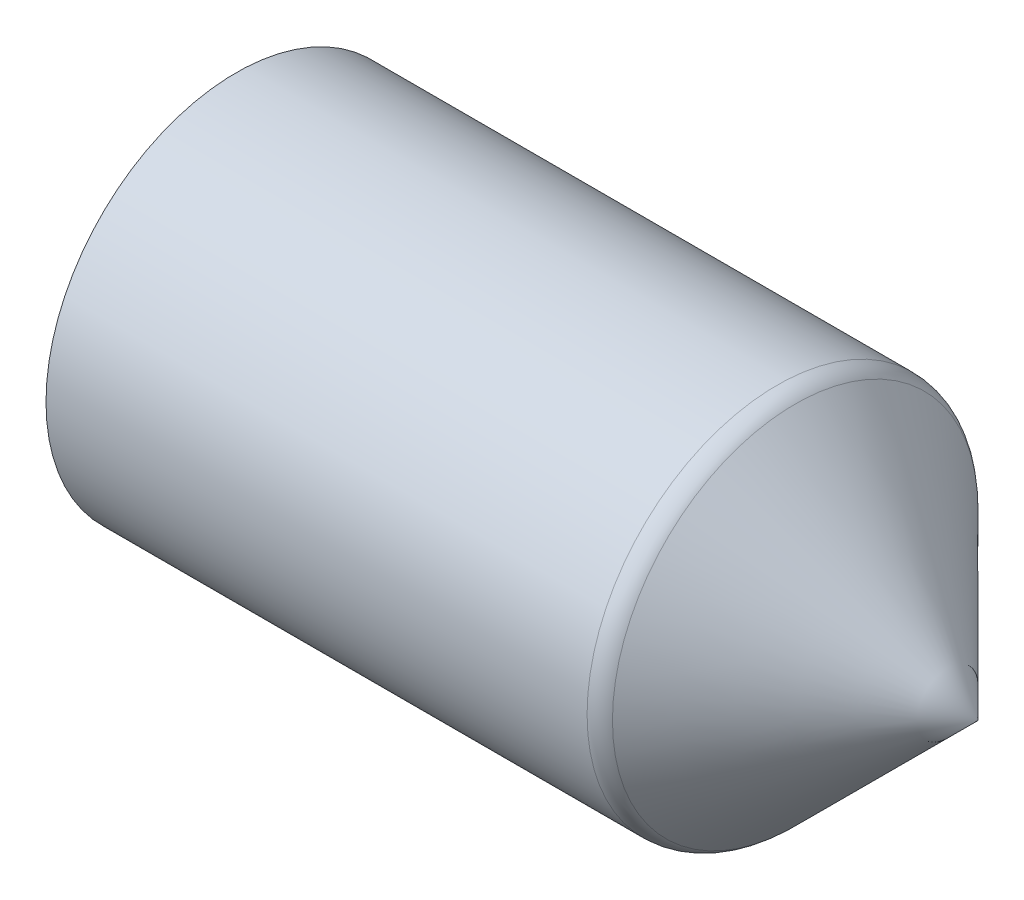
SolidWorks part; units mm, degrees
ref_plane "Front Plane" through (0, 0, 0) normal (0, 0, 1) x (1, 0, 0)
ref_plane "Top Plane" through (0, 0, 0) normal (0, 1, 0) x (1, 0, 0)
ref_plane "Right Plane" through (0, 0, 0) normal (1, 0, 0) x (0, 0, -1)
sketch "Sketch1" plane through (0, 0, 0) normal (0, 0, 1) x (1, 0, 0)
  line L0 (0, 1.5) -> (0, 0)
  line L1 (0, 0) -> (6, 0)
  line L2 (6, 0) -> (4.5, 1.5)
  line L3 (4.5, 1.5) -> (0, 1.5)
  dimension "D1" = 6
  dimension "D2" = 1.5
  dimension "D3" = 45
revolve "Revolve1" add sketch "Sketch1" angle 360 about L1
sketch "Sketch2" plane through (0, 0, 0) normal (-1, 0, 0) x (0, 0, 1)
  line L7 (0, -0.866) -> (0.75, -0.433)
  line L8 (0.75, -0.433) -> (0.75, 0.433)
  line L9 (0.75, 0.433) -> (0, 0.866)
  line L10 (0, 0.866) -> (-0.75, 0.433)
  line L11 (-0.75, 0.433) -> (-0.75, -0.433)
  line L12 (-0.75, -0.433) -> (0, -0.866)
  circle A0 centre (0, 0) radius 0.75 construction
  dimension "D1" = 1.5
extrude "Cut-Extrude1" cut sketch "Sketch2" against normal blind 2.1
chamfer "Chamfer1" distance 0.15 angle 60 1 edges at (0, 0, 1.5)
fillet "Fillet1" radius 0.2 1 edges at (4.5, 0, 1.5)
